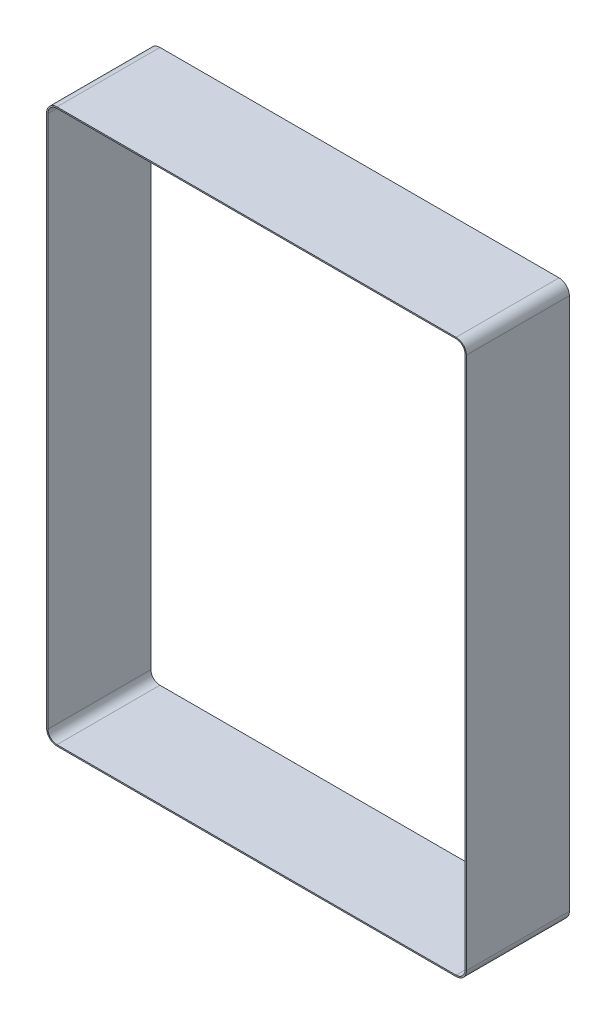
SolidWorks part; units mm, degrees
ref_plane "Front Plane" through (0, 0, 0) normal (0, 0, 1) x (1, 0, 0)
ref_plane "Top Plane" through (0, 0, 0) normal (0, 1, 0) x (1, 0, 0)
ref_plane "Right Plane" through (0, 0, 0) normal (1, 0, 0) x (0, 0, -1)
sketch "Sketch1" plane through (0, 0, 0) normal (0, 0, 1) x (1, 0, 0)
  line L0 (0, 253.9947) -> (0, -280.5371) construction
  line L1 (271.5203, 394.7232) -> (-281.4982, 394.7232) construction
  line L2 (273.0703, -33.2768) -> (-292.1624, -33.2768) construction
  line L3 (162, 68.1599) -> (162, -253.0072) construction
  line L4 (155, -26.2768) -> (155, -33.2768) construction
  line L5 (155, -26.2768) -> (162, -26.2768) construction
  line L6 (162, -26.2768) -> (162, 387.7232)
  line L8 (137.5, 380.7232) -> (-137.5, 380.7232) construction
  line L9 (155, 394.7232) -> (-155, 394.7232)
  line L10 (155, -33.2768) -> (-155, -33.2768)
  line L11 (-162, -26.2768) -> (-162, 387.7232)
  line L12 (155, -34.2768) -> (-155, -34.2768)
  line L13 (-163, -26.2768) -> (-163, 387.7232)
  line L14 (155, 395.7232) -> (-155, 395.7232)
  line L15 (163, -26.2768) -> (163, 387.7232)
  arc A0 (-155, 394.7232) -> (-162, 387.7232) centre (-155, 387.7232) ccw construction
  arc A1 (-162, -26.2768) -> (-155, -33.2768) centre (-155, -26.2768) ccw construction
  arc A3 (162, -26.2768) -> (155, -33.2768) centre (155, -26.2768) cw
  arc A4 (155, 394.7232) -> (162, 387.7232) centre (155, 387.7232) cw
  arc A5 (-155, 394.7232) -> (-162, 387.7232) centre (-155, 387.7232) ccw
  arc A6 (-162, -26.2768) -> (-155, -33.2768) centre (-155, -26.2768) ccw
  arc A7 (-163, -26.2768) -> (-155, -34.2768) centre (-155, -26.2768) ccw
  arc A8 (-155, 395.7232) -> (-163, 387.7232) centre (-155, 387.7232) ccw
  arc A9 (155, 395.7232) -> (163, 387.7232) centre (155, 387.7232) cw
  arc A10 (163, -26.2768) -> (155, -34.2768) centre (155, -26.2768) cw
  arc A11 (155, 394.7232) -> (162, 387.7232) centre (155, 387.7232) cw construction
  circle A14 centre (155, 387.7232) radius 7 construction
  circle A15 centre (-242.8735, 489.4461) radius 7 construction
  point P0 (0, 0)
  point P7 (0, 380.7232)
  point P27 (0, 352.7232)
  point P28 (0, -33.2768)
  point P31 (0, 394.7232)
  dimension "D2" = 7
  dimension "D3" = 7
  dimension "D5" = 14
  dimension "D1" = 1
extrude "Boss-Extrude1" add sketch "Sketch1" along normal blind 80 contours A10 L15 A9 L14 A4 L6 A3 L10 A6 L11 A5 A8 L13 A7 L12
ref_plane "Plane3" through (0, 0, 40) normal (0, 0, 1) x (1, 0, 0)
equation "\"Base-Width\"= 400"
equation "\"Base-Height\"= 300"
equation "\"Support-Rod-Diameter\"= 16"
equation "\"Support-Rod-X-Offset\"= 40"
equation "\"Support-Rod-Y-Offset\"= 30"
equation "\"Base-Thickness\" = 5"
equation "\"Base-Depth\"= 80"
